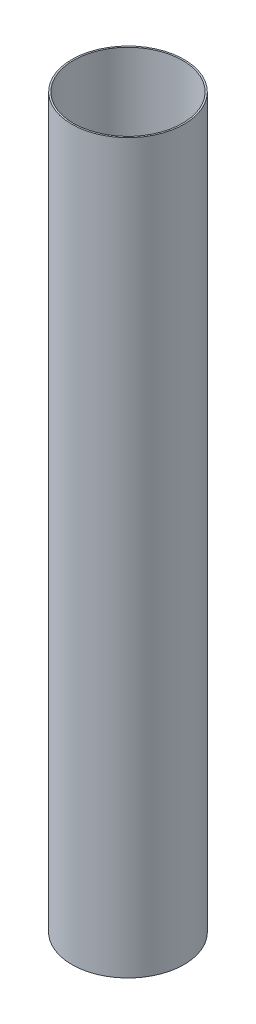
SolidWorks part; units mm, degrees
material "A-Glass Fiber"
ref_plane "Front Plane" through (0, 0, 0) normal (0, 0, 1) x (1, 0, 0)
ref_plane "Top Plane" through (0, 0, 0) normal (0, 1, 0) x (1, 0, 0)
ref_plane "Right Plane" through (0, 0, 0) normal (1, 0, 0) x (0, 0, -1)
sketch "Sketch1" plane through (0, 0, 0) normal (0, 1, 0) x (1, 0, 0)
  circle A0 centre (0, 0) radius 78.359
  circle A1 centre (0, 0) radius 76.2
  dimension "D1" = 152.4
  dimension "D2" = 156.718
extrude "Boss-Extrude1" add sketch "Sketch1" along normal blind 1016
